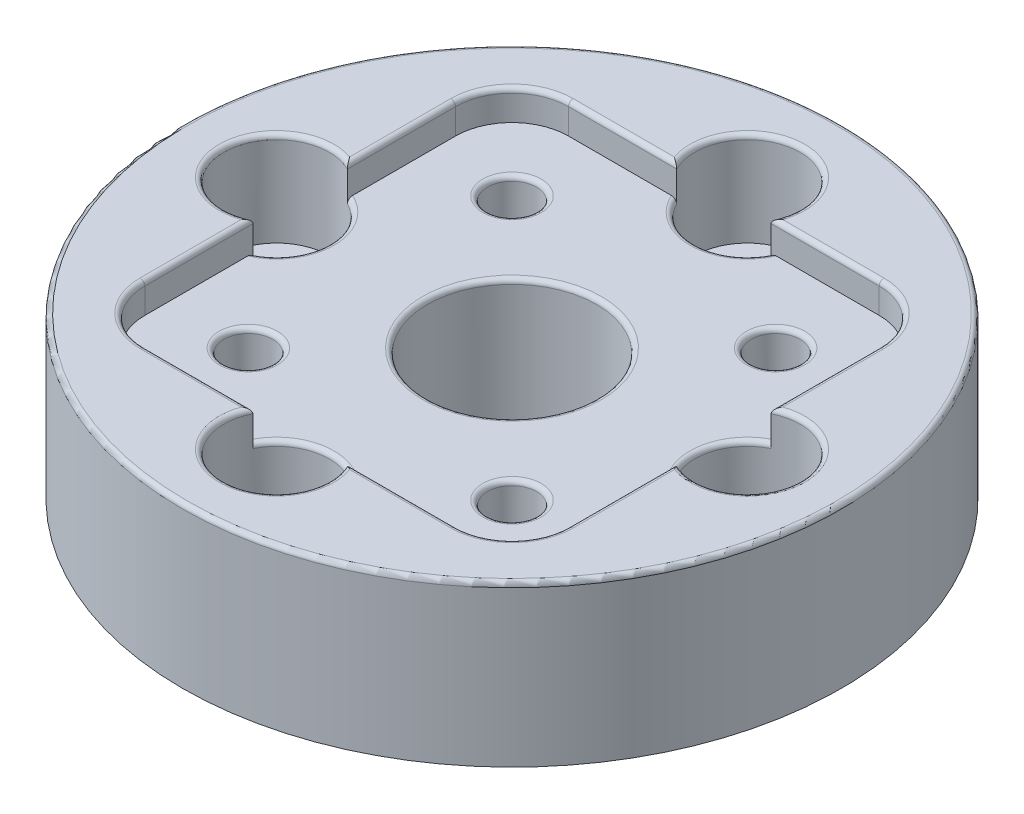
SolidWorks part; units mm, degrees
ref_plane "Front Plane" through (0, 0, 0) normal (0, 0, 1) x (1, 0, 0)
ref_plane "Top Plane" through (0, 0, 0) normal (0, 1, 0) x (1, 0, 0)
ref_plane "Right Plane" through (0, 0, 0) normal (1, 0, 0) x (0, 0, -1)
sketch "Sketch1" plane through (0, 0, 0) normal (0, 1, 0) x (1, 0, 0)
  circle A0 centre (0, 0) radius 12.5
  circle A1 centre (0, 0) radius 17.5
  circle A2 centre (0, 12.5) radius 1.5
  circle A3 centre (12.5, 0) radius 1.5
  circle A4 centre (0, -12.5) radius 1.5
  circle A5 centre (-12.5, 0) radius 1.5
  circle A6 centre (0, 0) radius 4.5
  dimension "D1" = 25
  dimension "D2" = 35
  dimension "D3" = 3
  dimension "D4" = 9
extrude "Boss-Extrude1" add sketch "Sketch1" along normal blind 8.5 contours A1 A5 A0 A2 A3 A4 | A5 A0 A4 A3 A2 A6
sketch "Sketch3" plane through (0, 8.5, 0) normal (0, 1, 0) x (1, 0, 0)
  circle A0 centre (0, 12.5) radius 2.8
  circle A1 centre (12.5, 0) radius 2.8
  circle A2 centre (0, -12.5) radius 2.8
  circle A3 centre (-12.5, 0) radius 2.8
  dimension "D1" = 5.6
extrude "Cut-Extrude2" cut sketch "Sketch3" against normal blind 5
sketch "Sketch2" plane through (0, 8.5, 0) normal (0, 1, 0) x (1, 0, 0)
  line L1 (-11.25, -11.25) -> (11.25, -11.25)
  line L2 (-11.25, -11.25) -> (-11.25, 11.25)
  line L3 (-11.25, 11.25) -> (11.25, 11.25)
  line L4 (11.25, -11.25) -> (11.25, 11.25)
  line L5 (-11.25, -11.25) -> (11.25, 11.25) construction
  line L6 (-11.25, 11.25) -> (11.25, -11.25) construction
  point P0 (0, 0)
  dimension "D1" = 22.5
extrude "Cut-Extrude1" cut sketch "Sketch2" against normal blind 1.6
sketch "Sketch4" plane through (0, 6.9, 0) normal (0, 1, 0) x (1, 0, 0)
  line L0 (0, 22.2187) -> (0, -23.772) construction
  line L1 (-23.8395, 0) -> (30.2553, 0) construction
  line L2 (7, 7) -> (0, 7) construction
  line L3 (7, 7) -> (7, 0) construction
  circle A0 centre (7, 7) radius 1.3
  circle A1 centre (-7, 7) radius 1.3
  circle A2 centre (7, -7) radius 1.3
  circle A3 centre (-7, -7) radius 1.3
  dimension "D1" = 2.6
  dimension "D2" = 14
extrude "Cut-Extrude3" cut sketch "Sketch4" against normal up to next
fillet "Fillet2" radius 3 4 edges at (-11.25, 7.7, 11.25) (11.25, 7.7, 11.25) (11.25, 7.7, -11.25) (-11.25, 7.7, -11.25)
fillet "Fillet1" radius 0.25 26 edges at (0, 8.5, 17.5) (15.3, 8.5, 0) (11.25, 8.5, 5.3777) (11.25, 8.5, -5.3777) (-5.3777, 8.5, -11.25) (5.3777, 8.5, -11.25) (0, 8.5, -15.3) (-11.25, 8.5, 5.3777) (-11.25, 8.5, -5.3777) (-15.3, 8.5, 0) (5.3777, 8.5, 11.25) (-5.3777, 8.5, 11.25) (0, 8.5, 15.3) (0, 6.9, -4.5) (0, 6.9, 9.7) (9.7, 6.9, 0) (0, 6.9, -9.7) (-9.7, 6.9, 0) (10.3713, 8.5, -10.3713) (-10.3713, 8.5, -10.3713) (-10.3713, 8.5, 10.3713) (10.3713, 8.5, 10.3713) (7, 6.9, -5.7) (7, 6.9, 5.7) (-7, 6.9, 8.3) (-7, 6.9, -8.3)
